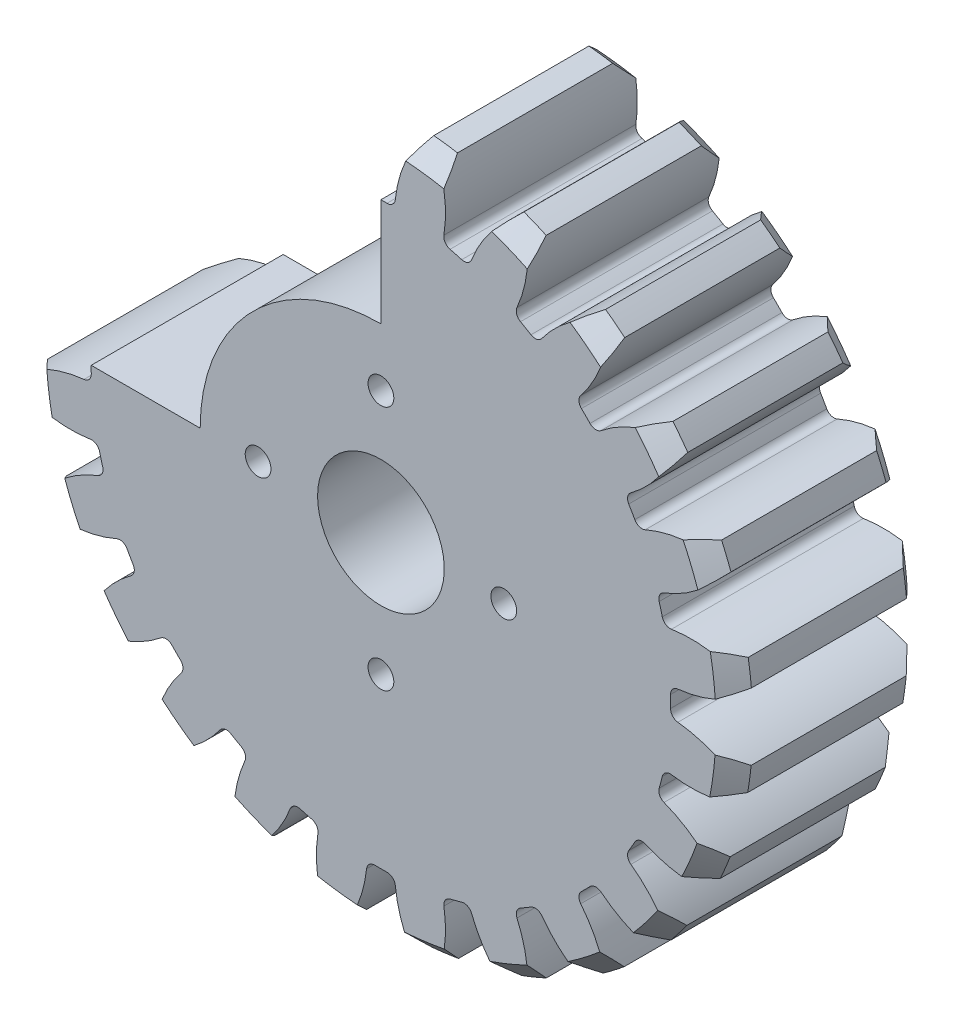
SolidWorks part; units mm, degrees
ref_plane "Plan de face" through (0, 0, 0) normal (0, 0, 1) x (1, 0, 0)
ref_plane "Plan de dessus" through (0, 0, 0) normal (0, 1, 0) x (1, 0, 0)
ref_plane "Plan de droite" through (0, 0, 0) normal (1, 0, 0) x (0, 0, -1)
sketch "Sketch1" plane through (0, 0, 0) normal (0, 0, 1) x (1, 0, 0)
  circle A0 centre (0, 0) radius 21.25 construction
  circle A1 centre (0, 0) radius 23.0208
  dimension "D1" = 42.5
  dimension "D2" = 46.0417
extrude "Boss-Extrude1" add sketch "Sketch1" along normal mid plane 12.5
sketch "Sketch2" plane through (0, 0, 6.25) normal (0, 0, 1) x (1, 0, 0)
  line L0 (0, 23.0208) -> (0, 0) construction
  line L1 (0, 0) -> (5.9582, 22.2364) construction
  line L2 (0, 0) -> (3.0048, 22.8239) construction
  line L3 (-0.8962, 18.7494) -> (0, 0) construction
  line L4 (-1.3898, 21.2045) -> (1.3898, 21.2045) construction
  line L5 (1.3898, 21.2045) -> (4.1457, 20.8417) construction
  line L6 (-2.0186, 22.9322) -> (0, 17.386) construction
  arc A0 (0.8962, 18.7494) -> (-0.8962, 18.7494) centre (0, 0) ccw
  circle A1 centre (0, 0) radius 19.4792 construction
  circle A2 centre (0, 0) radius 23.0208 construction
  arc A3 (2.2433, 22.9113) -> (0.8962, 18.7494) centre (9.2295, 18.3511) ccw
  arc A4 (-2.2433, 22.9113) -> (-0.8962, 18.7494) centre (-9.2295, 18.3511) cw
  circle A5 centre (0, 0) radius 23.0208 construction
  circle A6 centre (0, 0) radius 21.25 construction
  arc A7 (-2.2433, 22.9113) -> (2.2433, 22.9113) centre (0, 0) cw
  dimension "D1" = 15
  dimension "D2" = 3.5417
  dimension "D3" = 4.25
  dimension "D4" = 20
extrude "Cut-Extrude1" cut sketch "Sketch2" against normal through all
fillet "Fillet1" radius 0.5312 2 edges at (0.8962, 18.7494, 0) (-0.8962, 18.7494, 0)
chamfer "Chamfer1" distance 1.2 2 edges at (0, -23.0208, 6.25) (0, -23.0208, -6.25)
pattern_circular "CirPattern2" count 24 over 360 about axis through (0, -0.0957, 0) along (0, 0, 1) of "Fillet1", "Cut-Extrude1"
sketch "Sketch3" plane through (0, 0, -6.25) normal (0, 0, -1) x (-1, 0, 0)
  circle A0 centre (0, 0) radius 4.125
  circle A1 centre (0, 0) radius 8 construction
  circle A2 centre (0, 8) radius 0.8387
  circle A3 centre (8, 0) radius 0.8387
  circle A4 centre (0, -8) radius 0.8387
  circle A5 centre (-8, 0) radius 0.8387
  dimension "D1" = 8.25
  dimension "D2" = 16
  dimension "D3" = 1.6774
extrude "Cut-Extrude2" cut sketch "Sketch3" against normal through all
sketch "Sketch4" plane through (0, 0, -6.25) normal (0, 0, -1) x (-1, 0, 0)
  line L0 (0, 0) -> (0, 23.0208) construction
  line L1 (0, 0) -> (23.0208, 0) construction
  line L6 (11.7708, 0) -> (23.0208, 0)
  line L7 (0, 11.7708) -> (0, 23.0208)
  arc A2 (0, 11.7708) -> (11.7708, 0) centre (0, 0) cw
  circle A3 centre (0, 0) radius 23.0208 construction
  arc A5 (0, 23.0208) -> (23.0208, 0) centre (0, 0) cw
  dimension "D1" = 11.25
extrude "Cut-Extrude3" cut sketch "Sketch4" against normal through all
equation "\"Module\"= ( 4.25 / \"Number of teeth\" )"
equation "\"Number of teeth\" = 24"
equation "\"Pressure angle\"= 20"
equation "\"D1@Sketch1\"=\"Module\" * \"Number of teeth\""
equation "\"D2@Sketch1\"=(\"Number of teeth\" + 2) * \"Module\""
equation "\"D2@Sketch2\"=\"Module\"*2"
equation "\"D1@Fillet1\"=0.3*\"Module\""
equation "\"D1@Sketch2\"=360/\"Number of teeth\""
equation "\"D3@Sketch2\"=\"Module\"*2.4"
equation "\"D4@Sketch2\"=\"Pressure angle\""
equation "\"D1@CirPattern2\"=\"Number of teeth\""
